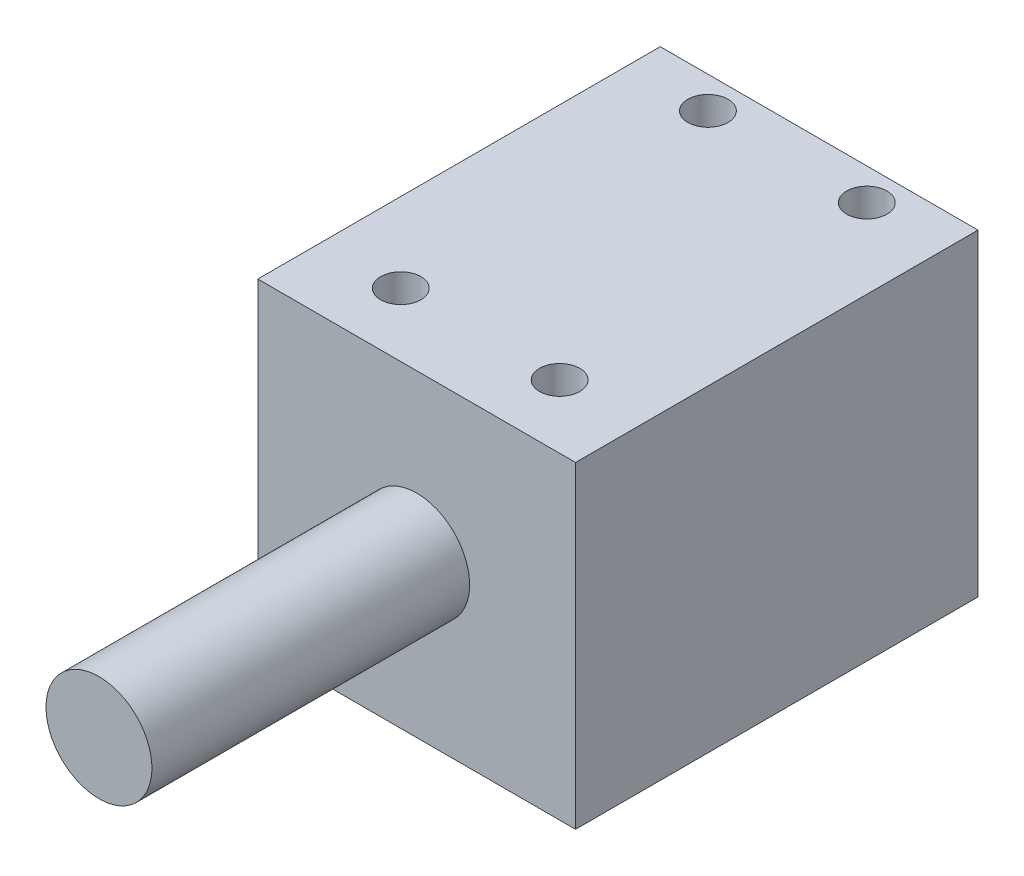
SolidWorks part; units mm, degrees
ref_plane "Front Plane" through (0, 0, 0) normal (0, 0, 1) x (1, 0, 0)
ref_plane "Top Plane" through (0, 0, 0) normal (0, 1, 0) x (1, 0, 0)
ref_plane "Right Plane" through (0, 0, 0) normal (1, 0, 0) x (0, 0, -1)
sketch "Sketch3" plane through (0, 0, 0) normal (0, 0, 1) x (1, 0, 0)
  line L1 (-19.05, -19.05) -> (19.05, -19.05)
  line L2 (-19.05, -19.05) -> (-19.05, 19.05)
  line L3 (-19.05, 19.05) -> (19.05, 19.05)
  line L4 (19.05, -19.05) -> (19.05, 19.05)
  line L5 (-19.05, -19.05) -> (19.05, 19.05) construction
  line L6 (-19.05, 19.05) -> (19.05, -19.05) construction
  point P0 (0, 0)
  dimension "D1" = 38.1
  dimension "D2" = 38.1
extrude "Boss-Extrude1" add sketch "Sketch3" against normal blind 48.26 contours L3 L4 L1 L2
sketch "Sketch4" plane through (0, 0, 0) normal (0, 0, 1) x (1, 0, 0)
  circle A0 centre (0, 0) radius 6.35
  dimension "D1" = 12.7
extrude "Boss-Extrude2" add sketch "Sketch4" along normal blind 38.1 contours A0
sketch "Sketch5" plane through (0, 19.05, 0) normal (0, 1, 0) x (1, 0, 0)
  line L1 (-9.525, 7.62) -> (9.525, 7.62) construction
  line L2 (-9.525, 7.62) -> (-9.525, 44.45) construction
  line L3 (-9.525, 44.45) -> (9.525, 44.45) construction
  line L4 (9.525, 7.62) -> (9.525, 44.45) construction
  line L5 (-9.525, 7.62) -> (9.525, 44.45) construction
  line L6 (-9.525, 44.45) -> (9.525, 7.62) construction
  line L7 (-19.05, 48.26) -> (19.05, 48.26) construction
  line L8 (-19.05, 48.26) -> (-19.05, 0) construction
  circle A0 centre (-9.525, 44.45) radius 2.413
  circle A1 centre (9.525, 44.45) radius 2.413
  circle A2 centre (9.525, 7.62) radius 2.413
  circle A3 centre (-9.525, 7.62) radius 2.413
  point P0 (0, 26.035)
  dimension "D5" = 4.826
  dimension "D6" = 4.826
  dimension "D7" = 4.826
  dimension "D8" = 4.826
  dimension "D1" = 3.81
  dimension "D2" = 19.05
  dimension "D3" = 36.83
  dimension "D4" = 19.05
extrude "Cut-Extrude1" cut sketch "Sketch5" against normal blind 10.16
